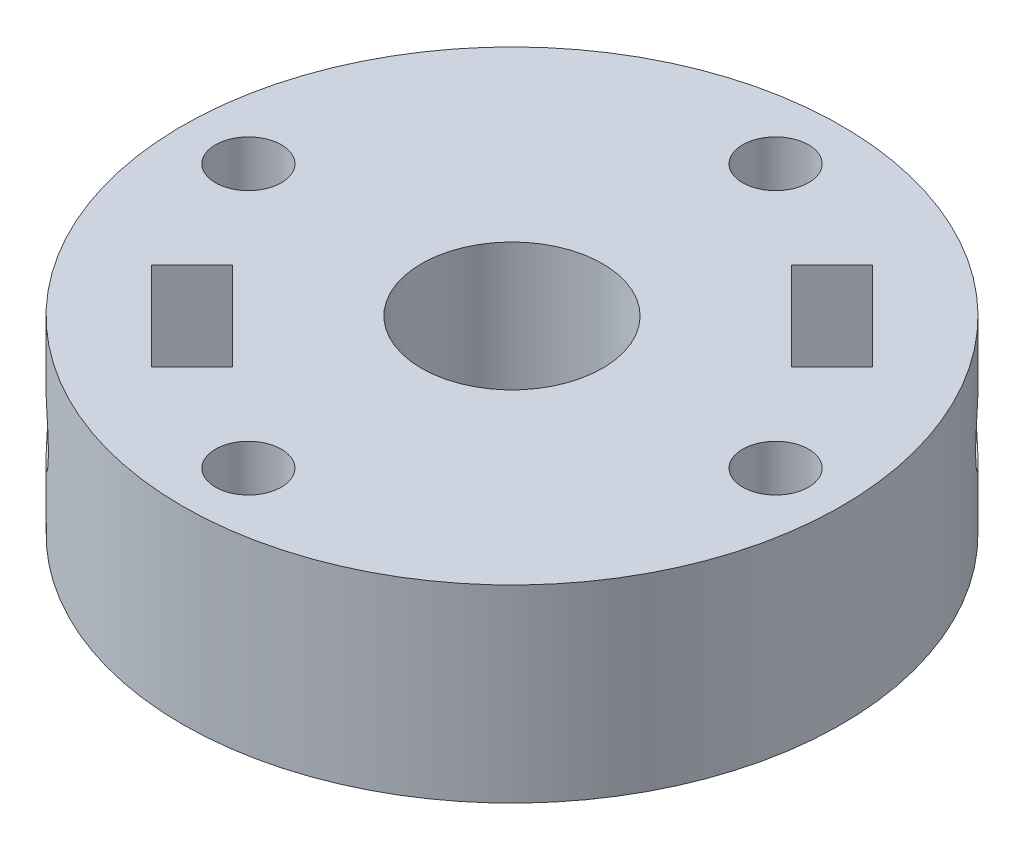
SolidWorks part; units mm, degrees
ref_plane "Front Plane" through (0, 0, 0) normal (0, 0, 1) x (1, 0, 0)
ref_plane "Top Plane" through (0, 0, 0) normal (0, 1, 0) x (1, 0, 0)
ref_plane "Right Plane" through (0, 0, 0) normal (1, 0, 0) x (0, 0, -1)
sketch "Sketch1" plane through (0, 0, 0) normal (0, 1, 0) x (1, 0, 0)
  circle A0 centre (0, 0) radius 4.125
  circle A1 centre (0, 0) radius 12 construction
  circle A2 centre (0, 12) radius 1.5
  circle A3 centre (12, 0) radius 1.5
  circle A4 centre (0, -12) radius 1.5
  circle A5 centre (-12, 0) radius 1.5
  circle A6 centre (0, 0) radius 15
  dimension "D1" = 8.25
  dimension "D2" = 24
  dimension "D3" = 3
  dimension "D4" = 30
extrude "Boss-Extrude1" add sketch "Sketch1" along normal blind 8.6
sketch "Sketch2" plane through (0, 8.6, 0) normal (0, 1, 0) x (1, 0, 0)
  line L0 (0, 0) -> (10.6066, 10.6066) construction
  line L1 (8.2024, 8.2024) -> (6.1872, 10.2177)
  line L2 (6.1872, 10.2177) -> (4.3487, 8.3792)
  line L3 (4.3487, 8.3792) -> (8.3792, 4.3487)
  line L4 (0, 0) -> (15, 0) construction
  line L5 (10.2177, 6.1872) -> (8.3792, 4.3487)
  line L6 (8.2024, 8.2024) -> (10.2177, 6.1872)
  line L7 (0, 0) -> (-9.8622, 9.8622) construction
  line L8 (-10.2177, -6.1872) -> (-8.3792, -4.3487)
  line L9 (-8.2024, -8.2024) -> (-10.2177, -6.1872)
  line L10 (-8.2024, -8.2024) -> (-6.1872, -10.2177)
  line L11 (-6.1872, -10.2177) -> (-4.3487, -8.3792)
  line L12 (-8.3792, -4.3487) -> (-4.3487, -8.3792)
  circle A0 centre (0, 0) radius 15 construction
  point P12 (6.364, 6.364)
  point P13 (0, 0)
  dimension "D1" = 45
  dimension "D2" = 5.7
  dimension "D3" = 2.6
  dimension "D4" = 135
  dimension "D5" = 9
extrude "Cut-Extrude1" cut sketch "Sketch2" against normal blind 8.6
sketch "Sketch3" plane through (6.364, 0, -6.364) normal (0.7071, 0, -0.7071) x (-0.7071, 0, -0.7071)
  line L0 (0, 8.6) -> (0, 0) construction
  line L1 (15, 8.6) -> (-15, 8.6) construction
  circle A0 centre (0, 4.3) radius 1.5
  dimension "D1" = 3
extrude "Cut-Extrude2" cut sketch "Sketch3" against normal blind 30 and the other way blind 8.6
